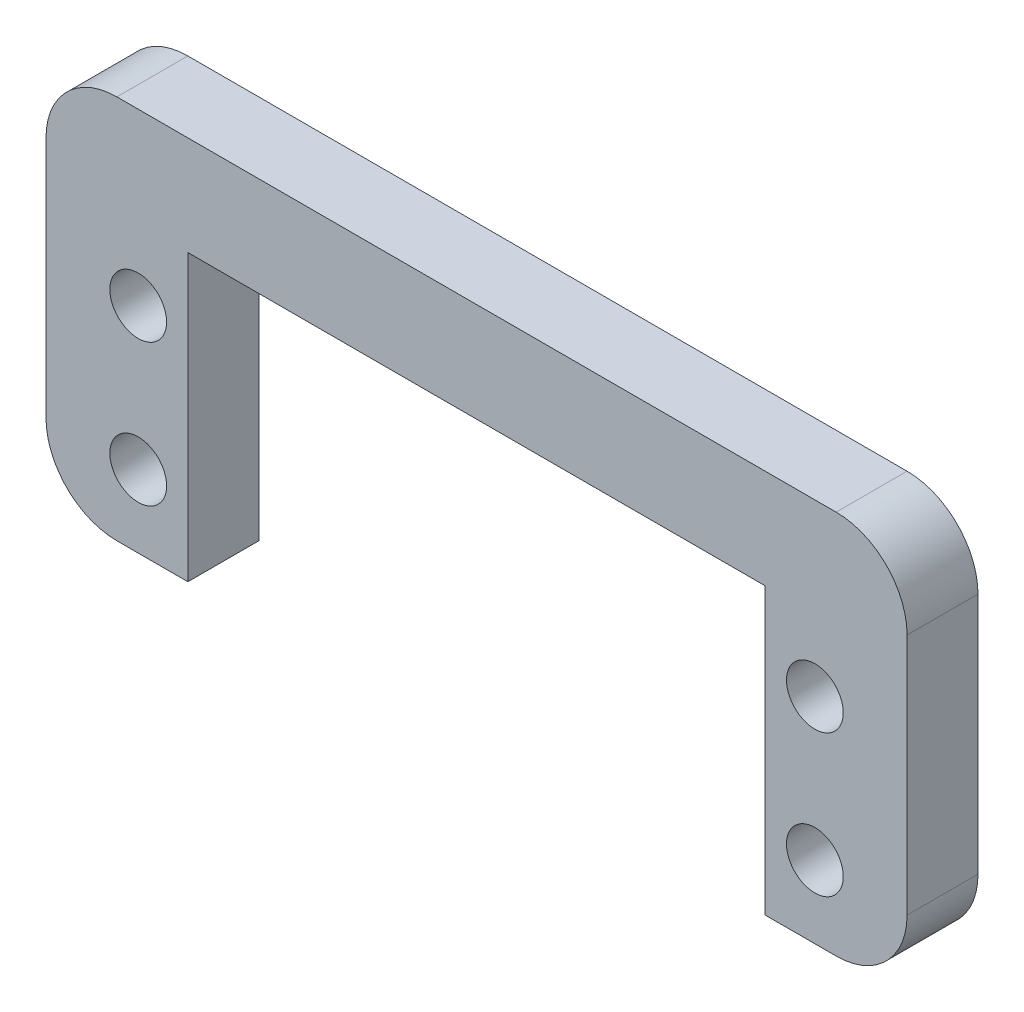
SolidWorks part; units mm, degrees
ref_plane "Front Plane" through (0, 0, 0) normal (1, 0, 0) x (0, 1, 0)
ref_plane "Top Plane" through (0, 0, 0) normal (0, 0, 1) x (0, 1, 0)
ref_plane "Right Plane" through (0, 0, 0) normal (0, 1, 0) x (-1, 0, 0)
sketch "Sketch1" plane through (0, 0, 0) normal (0, 0, 1) x (0, 1, 0)
  line L0 (-10.05, 20.35) -> (10.05, 20.35)
  line L1 (10.05, 20.35) -> (-10.05, 20.35) construction
  line L2 (10.05, 20.35) -> (10.05, -20.35) construction
  line L3 (10.05, -20.35) -> (-10.05, -20.35) construction
  line L4 (-10.05, 20.35) -> (-10.05, -20.35) construction
  line L5 (10.05, 20.35) -> (-10.05, -20.35) construction
  line L6 (10.05, -20.35) -> (-10.05, 20.35) construction
  line L7 (10.05, 20.35) -> (10.05, -20.35)
  line L8 (10.05, -20.35) -> (-10.05, -20.35)
  line L9 (-5.05, 30.35) -> (12.05, 30.35)
  line L10 (-55, 0) -> (55, 0) construction
  line L11 (-5.05, -30.35) -> (12.05, -30.35)
  line L12 (17.05, 25.35) -> (17.05, -25.35)
  line L13 (-10.05, 25.35) -> (-10.05, 20.35)
  line L15 (-10.05, -25.35) -> (-10.05, -20.35)
  arc A0 (-5.05, 30.35) -> (-10.05, 25.35) centre (-5.05, 25.35) ccw
  arc A1 (-5.05, -30.35) -> (-10.05, -25.35) centre (-5.05, -25.35) cw
  arc A2 (12.05, -30.35) -> (17.05, -25.35) centre (12.05, -25.35) ccw
  arc A3 (12.05, 30.35) -> (17.05, 25.35) centre (12.05, 25.35) cw
  circle A4 centre (5.05, 23.85) radius 2
  circle A5 centre (-4.95, 23.85) radius 2
  circle A6 centre (5.05, -23.85) radius 2
  circle A7 centre (-4.95, -23.85) radius 2
  point P0 (0, 0)
  point P14 (-10.05, 30.35)
  point P17 (-10.05, -30.35)
  point P20 (17.05, -30.35)
  point P23 (17.05, 30.35)
  point P28 (0, 0)
  dimension "D5" = 5
  dimension "D6" = 4
  dimension "D8" = 10
  dimension "D1" = 40.7
  dimension "D2" = 20.1
  dimension "D3" = 10
  dimension "D4" = 27.1
  dimension "D7" = 5
  dimension "D9" = 3.5
extrude "Boss-Extrude1" add sketch "Sketch1" against normal blind 5
